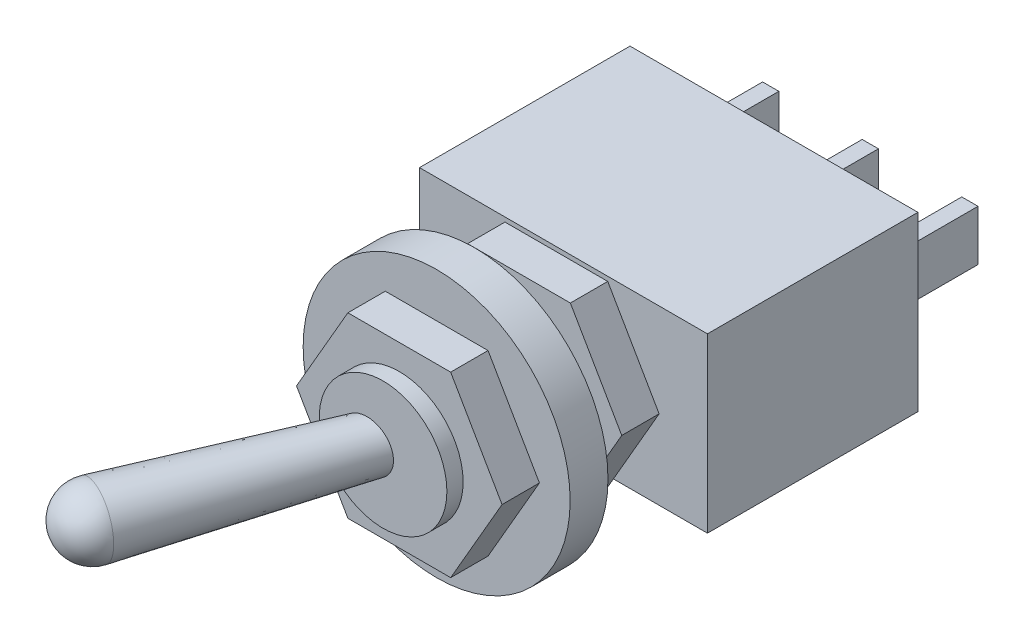
SolidWorks part; units mm, degrees
ref_plane "Front Plane" through (0, 0, 0) normal (0, 0, 1) x (1, 0, 0)
ref_plane "Top Plane" through (0, 0, 0) normal (0, 1, 0) x (1, 0, 0)
ref_plane "Right Plane" through (0, 0, 0) normal (1, 0, 0) x (0, 0, -1)
sketch "Sketch1" plane through (0, 0, 0) normal (0, 0, 1) x (1, 0, 0)
  line L1 (-6.47, -3.88) -> (6.47, -3.88)
  line L2 (-6.47, -3.88) -> (-6.47, 3.88)
  line L3 (-6.47, 3.88) -> (6.47, 3.88)
  line L4 (6.47, -3.88) -> (6.47, 3.88)
  line L5 (-6.47, -3.88) -> (6.47, 3.88) construction
  line L6 (-6.47, 3.88) -> (6.47, -3.88) construction
  point P0 (0, 0)
  dimension "D1" = 7.76
  dimension "D2" = 12.94
extrude "Boss-Extrude1" add sketch "Sketch1" along normal blind 9.46
sketch "Sketch2" plane through (0, 0, 9.46) normal (0, 0, 1) x (1, 0, 0)
  circle A0 centre (0, 0) radius 2.87
  dimension "D1" = 5.74
extrude "Boss-Extrude2" add sketch "Sketch2" along normal blind 8.11
sketch "Sketch3" plane through (0, 0, 0) normal (0, 1, 0) x (1, 0, 0)
  line L0 (0.4687, -17.57) -> (-2.5641, -27.1116)
  line L1 (-2.87, -17.57) -> (2.87, -17.57) construction
  line L2 (-5.3584, -26.1659) -> (-2.27, -17.57) construction
  line L3 (-2.27, -17.57) -> (0.2174, -18.3606) construction
  line L4 (-5.3584, -26.1659) -> (-2.5641, -27.1116) construction
  line L5 (-4.4688, -28.0531) -> (-0.7024, -17.57)
  line L6 (-4.4688, -28.0531) -> (-3.4316, -28.4258) construction
  line L7 (-3.4316, -28.4258) -> (0.4687, -17.57) construction
  line L8 (-2.27, -17.57) -> (-2.87, -17.57) construction
  line L9 (-6.47, -9.46) -> (-6.47, 0) construction
  line L10 (-0.7024, -17.57) -> (0.4687, -17.57)
  line L11 (-3.97, -28.14) -> (-3.97, -9.46) construction
  line L12 (-6.47, -9.46) -> (6.47, -9.46) construction
  arc A0 (-2.5641, -27.1116) -> (-4.4688, -28.0531) centre (-3.97, -26.6647) cw
  arc A1 (-5.3584, -26.1659) -> (-4.4688, -28.0531) centre (-3.97, -26.6647) ccw construction
  dimension "D1" = 2.61
  dimension "D2" = 2.95
  dimension "D3" = 2.5
  dimension "D4" = 0.6
  dimension "D5" = 18.68
revolve "Revolve1" add sketch "Sketch3" angle 360 about L5
sketch "Sketch4" plane through (0, 0, 0) normal (0, 0, -1) x (-1, 0, 0)
  line L0 (-4.475, 0) -> (0, 0) construction
  line L1 (0.365, -1.135) -> (-0.365, -1.135)
  line L2 (0.365, -1.135) -> (0.365, 1.135)
  line L3 (0.365, 1.135) -> (-0.365, 1.135)
  line L4 (-0.365, -1.135) -> (-0.365, 1.135)
  line L5 (0.365, -1.135) -> (-0.365, 1.135) construction
  line L6 (0.365, 1.135) -> (-0.365, -1.135) construction
  line L7 (-4.11, -1.135) -> (-4.84, -1.135)
  line L8 (-4.11, -1.135) -> (-4.11, 1.135)
  line L9 (-4.11, 1.135) -> (-4.84, 1.135)
  line L10 (-4.84, -1.135) -> (-4.84, 1.135)
  line L11 (-4.11, -1.135) -> (-4.84, 1.135) construction
  line L12 (-4.11, 1.135) -> (-4.84, -1.135) construction
  line L13 (4.84, -1.135) -> (4.11, -1.135)
  line L14 (4.84, -1.135) -> (4.84, 1.135)
  line L15 (4.84, 1.135) -> (4.11, 1.135)
  line L16 (4.11, -1.135) -> (4.11, 1.135)
  line L17 (4.84, -1.135) -> (4.11, 1.135) construction
  line L18 (4.84, 1.135) -> (4.11, -1.135) construction
  line L19 (0, 0) -> (4.475, 0) construction
  point P0 (0, 0)
  point P6 (-4.475, 0)
  point P11 (4.475, 0)
  dimension "D1" = 0.73
  dimension "D2" = 2.27
  dimension "D3" = 9.68
extrude "Boss-Extrude3" add sketch "Sketch4" along normal blind 4.33
ref_plane "Plane1" through (0, 0, 11.46) normal (0, 0, 1) x (1, 0, 0)
ref_plane "Plane2" through (0, 0, 13.46) normal (0, 0, 1) x (1, 0, 0)
sketch "Sketch5" plane through (0, 0, 11.46) normal (0, 0, 1) x (1, 0, 0)
  line L1 (-2.3094, -4) -> (2.3094, -4)
  line L2 (2.3094, -4) -> (4.6188, 0)
  line L3 (4.6188, 0) -> (2.3094, 4)
  line L4 (2.3094, 4) -> (-2.3094, 4)
  line L5 (-2.3094, 4) -> (-4.6188, 0)
  line L6 (-4.6188, 0) -> (-2.3094, -4)
  circle A0 centre (0, 0) radius 4 construction
  dimension "D1" = 8
extrude "Boss-Extrude4" add sketch "Sketch5" against normal blind 1.68
sketch "Sketch6" plane through (0, 0, 13.46) normal (0, 0, 1) x (1, 0, 0)
  circle A0 centre (0, 0) radius 6
  dimension "D1" = 12
extrude "Boss-Extrude5" add sketch "Sketch6" along normal blind 1.7
sketch "Sketch7" plane through (0, 0, 15.16) normal (0, 0, 1) x (1, 0, 0)
  line L0 (2.3094, 4) -> (-2.3094, 4) construction
  line L1 (-2.3094, -4) -> (2.3094, -4)
  line L2 (2.3094, -4) -> (4.6188, 0)
  line L3 (4.6188, 0) -> (2.3094, 4)
  line L4 (2.3094, 4) -> (-2.3094, 4)
  line L5 (-2.3094, 4) -> (-4.6188, 0)
  line L6 (-4.6188, 0) -> (-2.3094, -4)
  circle A0 centre (0, 0) radius 4 construction
extrude "Boss-Extrude6" add sketch "Sketch7" along normal blind 1.68
sketch "Sketch8" plane through (0, 0, 16.84) normal (0, 0, 1) x (1, 0, 0)
  line L0 (2.3094, -4) -> (4.6188, 0) construction
  circle A0 centre (0, 0) radius 4
